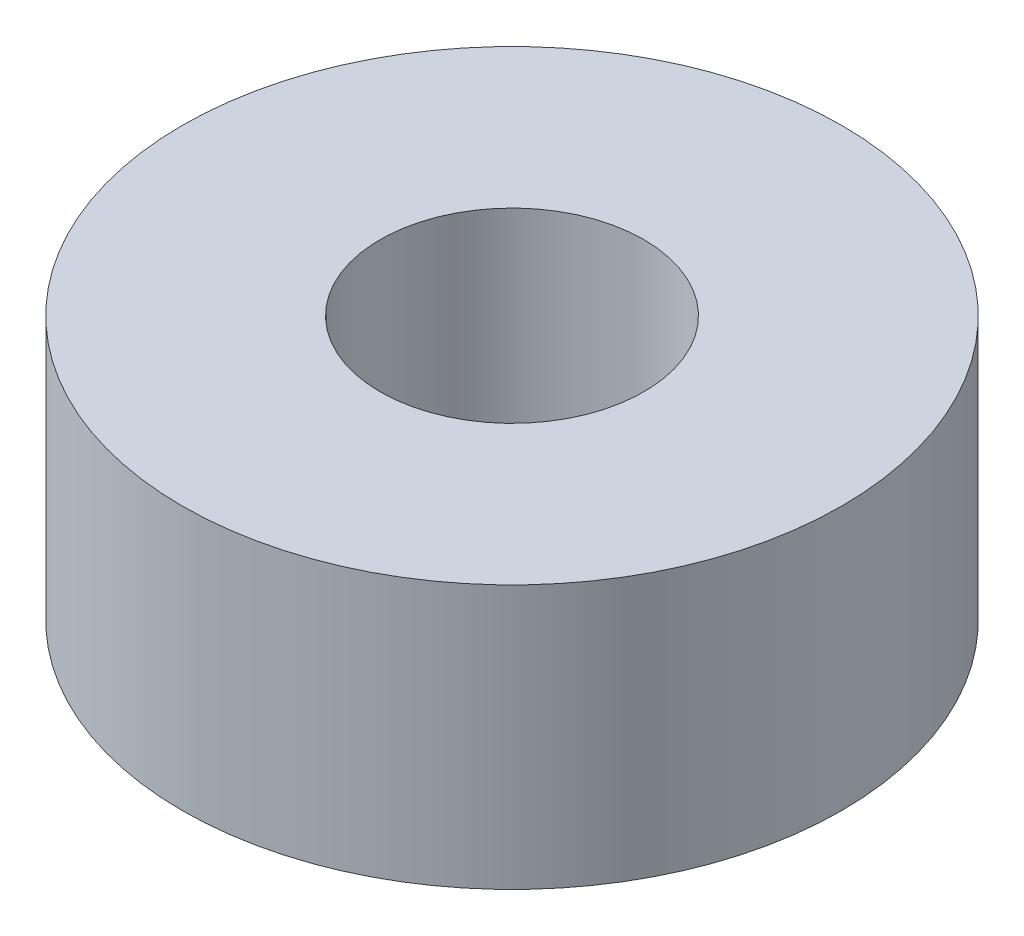
SolidWorks part; units mm, degrees
material "AISI 1035 钢 (SS)"
ref_plane "前视基准面" through (0, 0, 0) normal (0, 0, 1) x (1, 0, 0)
ref_plane "上视基准面" through (0, 0, 0) normal (0, 1, 0) x (1, 0, 0)
ref_plane "右视基准面" through (0, 0, 0) normal (1, 0, 0) x (0, 0, -1)
other "Configuration Table"
sketch "草图1" plane through (0, 0, 0) normal (0, 1, 0) x (1, 0, 0)
  circle A0 centre (0, 0) radius 5
  circle A1 centre (0, 0) radius 2
  dimension "D1" = 4
  dimension "D2" = 10
extrude "凸台-拉伸1" add sketch "草图1" along normal blind 4 contours A0 | A1
